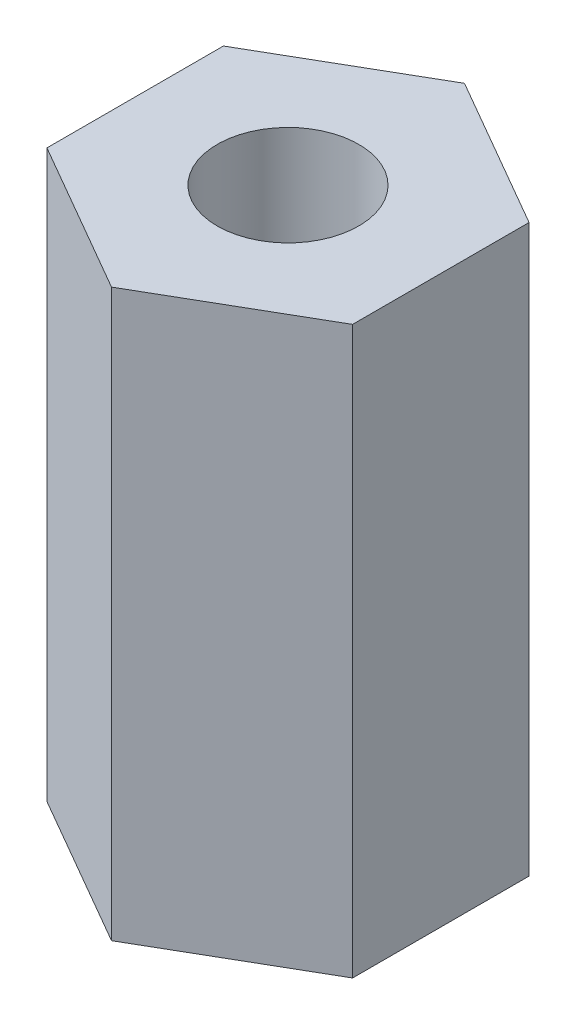
SolidWorks part; units mm, degrees
material "Plain Carbon Steel"
ref_plane "Front Plane" through (0, 0, 0) normal (0, 0, 1) x (1, 0, 0)
ref_plane "Top Plane" through (0, 0, 0) normal (0, 1, 0) x (1, 0, 0)
ref_plane "Right Plane" through (0, 0, 0) normal (1, 0, 0) x (0, 0, -1)
sketch "Sketch1" plane through (0, 0, 0) normal (0, 1, 0) x (1, 0, 0)
  line L1 (0, 3.1177) -> (-2.7, 1.5588)
  line L2 (-2.7, 1.5588) -> (-2.7, -1.5588)
  line L3 (-2.7, -1.5588) -> (0, -3.1177)
  line L4 (0, -3.1177) -> (2.7, -1.5588)
  line L5 (2.7, -1.5588) -> (2.7, 1.5588)
  line L6 (2.7, 1.5588) -> (0, 3.1177)
  circle A0 centre (0, 0) radius 2.7 construction
  dimension "D1" = 5.4
extrude "Boss-Extrude1" add sketch "Sketch1" along normal blind 10
hole_wizard "M3x0.5 Tapped Hole2" positions "Sketch6" profile "Sketch5" tap size "M3x0.5" standard "ANSI Metric" end condition through all
sketch "Sketch6" plane through (0, 10, 0) normal (0, 1, 0) x (1, 0, 0)
  point P0 (0, 0)
sketch "Sketch5" plane through (0, 10, 0) normal (1, 0, 0) x (0, 0, 1)
  line L0 (0, 0) -> (0, 10)
  line L1 (0, 10) -> (1.25, 10)
  line L2 (1.25, 10) -> (1.25, 0)
  line L5 (1.25, 0) -> (0, 0)
  line L11 (0, -6.35) -> (0, 107.95) construction
  dimension "Thru Tap Drill Dia." = 2.5
  dimension "Thru Tap Drill Depth" = 10
cosmetic thread "Hole Thread2"
